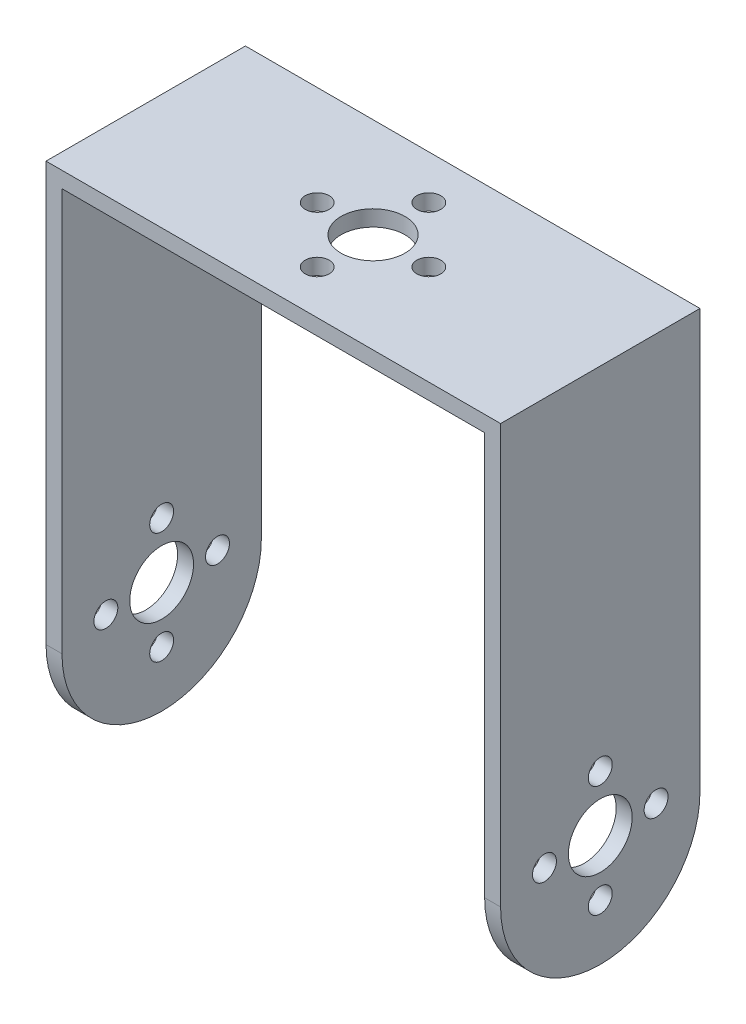
SolidWorks part; units mm, degrees
material "1060 Alloy"
ref_plane "Front Plane" through (0, 0, 0) normal (0, 0, 1) x (1, 0, 0)
ref_plane "Top Plane" through (0, 0, 0) normal (0, 1, 0) x (1, 0, 0)
ref_plane "Right Plane" through (0, 0, 0) normal (1, 0, 0) x (0, 0, -1)
sketch "Sketch3" plane through (0, 0, 0) normal (0, 0, 1) x (1, 0, 0)
  line L0 (-79.9255, 45.3865) -> (-27.043, 45.3865)
  line L1 (-81.9255, 45.3865) -> (-79.9255, 45.3865)
  line L2 (-81.9255, 45.3865) -> (-81.9255, -19.6135)
  line L3 (-81.9255, -19.6135) -> (-79.9255, -19.6135)
  line L4 (-79.9255, 43.39) -> (-79.9255, -19.6135)
  line L5 (-81.9255, 45.3865) -> (-79.9255, -19.6135) construction
  line L6 (-81.9255, -19.6135) -> (-79.9255, 45.3865) construction
  line L7 (-79.9255, 43.39) -> (-26.9255, 43.39)
  line L8 (-26.9255, 43.39) -> (-26.9255, -19.6135)
  line L9 (-27.043, 45.3865) -> (-24.9255, 45.3865)
  line L10 (-26.9255, -19.6135) -> (-24.9255, -19.6135)
  line L11 (-24.9255, 45.3865) -> (-24.9255, -19.6135)
  point P0 (-80.9255, 12.8865)
  dimension "D1" = 65
  dimension "D2" = 2
  dimension "D3" = 2
  dimension "D4" = 57
  dimension "D5" = 2
extrude "Boss-Extrude2" add sketch "Sketch3" along normal blind 25
sketch "Sketch4" plane through (0, 45.3865, 0) normal (0, 1, 0) x (1, 0, 0)
  line L0 (-81.9255, -25) -> (-81.9255, 0) construction
  line L3 (-24.9255, -25) -> (-81.9255, -25) construction
  circle A0 centre (-53.4255, -12.5) radius 4
  dimension "D1" = 28.5
  dimension "D3" = 8
  dimension "D2" = 12.5
extrude "Cut-Extrude1" cut sketch "Sketch4" against normal through all
sketch "Sketch6" plane through (-81.9255, 0, 0) normal (-1, 0, 0) x (0, 0, 1)
  line L1 (25, 45.3865) -> (0, 45.3865) construction
  line L2 (0, 45.3865) -> (0, -19.6135) construction
  circle A0 centre (12.5, -5.6135) radius 4
  dimension "D1" = 51
  dimension "D2" = 12.5
extrude "Cut-Extrude2" cut sketch "Sketch6" against normal through all
sketch "Sketch8" plane through (-81.9255, 0, 0) normal (-1, 0, 0) x (0, 0, 1)
  line L0 (25, 45.3865) -> (25, -19.6135) construction
  line L1 (25, -19.6135) -> (0, -19.6135) construction
  line L2 (0, 45.3865) -> (0, -19.6135) construction
  line L3 (25, -19.6135) -> (0, -19.6135)
  line L4 (0, 45.3865) -> (0, -19.6135)
  line L5 (25, 45.3865) -> (25, -19.6135)
  circle A0 centre (12.5, -7.1135) radius 12.5
  line M4 (0, -19.6135) -> (25, -19.6135)
  line M5 (25, -19.6135) -> (25, 45.3865)
extrude "Cut-Extrude3" cut sketch "Sketch8" against normal through all contours A0 L4 M4 | A0 L3 M5
sketch "Sketch9" plane through (-24.9255, 0, 0) normal (1, 0, 0) x (0, 0, -1)
  line L0 (0, 45.3865) -> (0, -7.1135) construction
  circle A0 centre (-12.5, -12.6135) radius 1.5
  arc A1 (-25, -7.1135) -> (0, -7.1135) centre (-12.5, -7.1135) ccw construction
  circle A2 centre (-19.5, -5.6135) radius 1.5
  circle A3 centre (-5.5, -5.6135) radius 1.5
  circle A4 centre (-12.5, 1.3865) radius 1.5
  point P0 (28.9827, -4.393)
  point P5 (-12.5, -19.6135)
  point P13 (-12.5, -5.6135)
  point P15 (-12.5, -5.6135)
  dimension "D1" = 4
  dimension "D4" = 7
  dimension "D3" = 3
  dimension "D2" = 7
  dimension "D5" = 14
  dimension "D6" = 12.5
extrude "Cut-Extrude4" cut sketch "Sketch9" against normal through all
sketch "Sketch10" plane through (0, 45.3865, 0) normal (0, 1, 0) x (1, 0, 0)
  line L0 (-24.9255, -25) -> (-81.9255, -25) construction
  line L3 (-24.9255, -25) -> (-24.9255, 0) construction
  circle A0 centre (-46.4255, -12.5) radius 1.5
  circle A2 centre (-53.4255, -5.5) radius 1.5
  circle A3 centre (-53.4255, -19.5) radius 1.5
  circle A4 centre (-60.4255, -12.5) radius 1.5
  point P0 (-81.9255, -11.0075)
  point P13 (-54.9255, -13.5)
  point P16 (-53.4255, -12.5)
  dimension "D1" = 4
  dimension "D3" = 5.5
  dimension "D4" = 28.5
  dimension "D5" = 3
  dimension "D2" = 7
extrude "Cut-Extrude5" cut sketch "Sketch10" against normal through all
